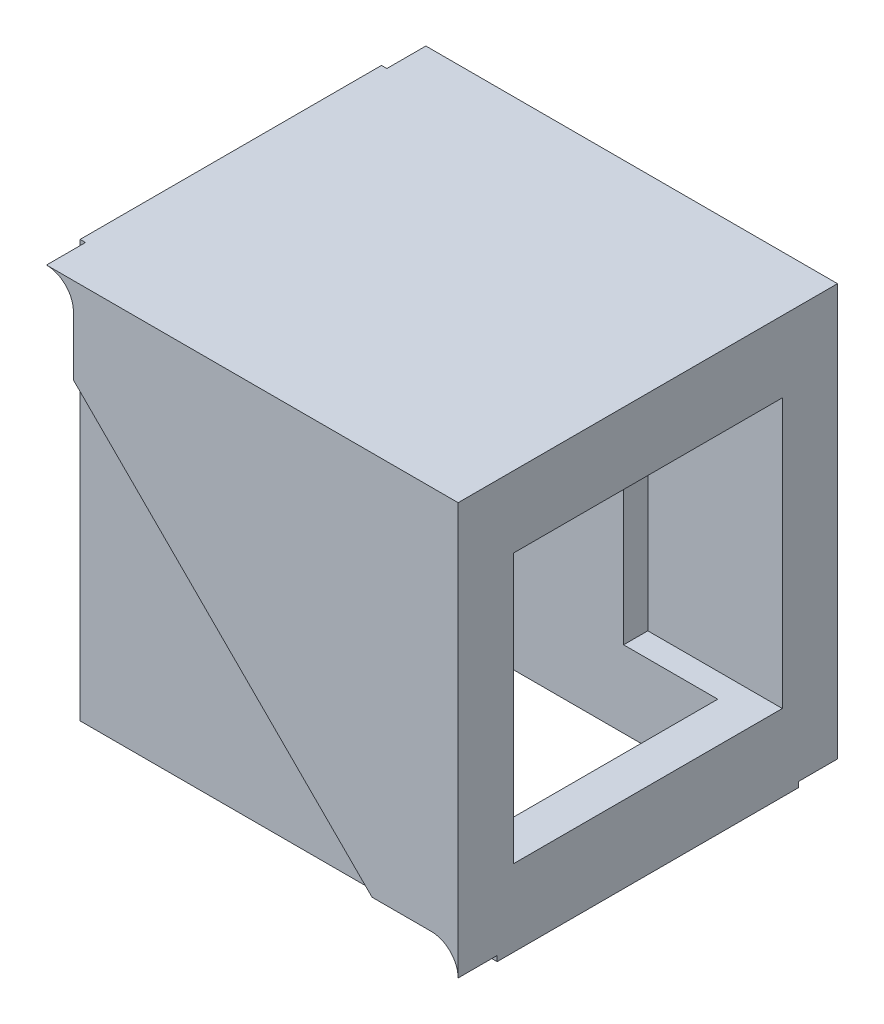
SolidWorks part; units mm, degrees
ref_plane "前视基准面" through (0, 0, 0) normal (0, 0, 1) x (1, 0, 0)
ref_plane "上视基准面" through (0, 0, 0) normal (0, 1, 0) x (1, 0, 0)
ref_plane "右视基准面" through (0, 0, 0) normal (1, 0, 0) x (0, 0, -1)
other "Configuration Table"
ref_plane "基准面1" through (835, 815, -2.8) normal (0, 0, 1) x (-1, 0, 0)
ref_plane "基准面2" through (835, 815, -25.2) normal (0, 0, 1) x (-1, 0, 0)
sketch "草图5" plane through (835, 815, -2.8) normal (0, 0, 1) x (-1, 0, 0)
  line L0 (831, 811) -> (831, 780) construction
  line L1 (800, 811) -> (831, 811) construction
  line L2 (831, 811) -> (831, 780)
  line L3 (800, 811) -> (831, 811)
  line L4 (831, 780) -> (800, 780)
  line L5 (800, 811) -> (800, 780)
extrude "凸台-拉伸1" add sketch "草图5" against normal blind 3
sketch "草图6" plane through (835, 815, -25.2) normal (0, 0, 1) x (-1, 0, 0)
  line L4 (831, 811) -> (800, 811)
  line L5 (831, 780) -> (831, 811)
  line L6 (800, 780) -> (831, 780)
  line L7 (800, 811) -> (800, 780)
  line L8 (831, 811) -> (800, 811)
  line L9 (831, 780) -> (831, 811)
  line L10 (800, 780) -> (831, 780)
  line L11 (800, 811) -> (800, 780)
  dimension "D1" = 0
extrude "凸台-拉伸2" add sketch "草图6" along normal blind 3 separate body
sketch "草图7" plane through (0, 0, -25.2) normal (0, 0, -1) x (-1, 0, 0)
  line L0 (-6.4, 28.6) -> (-28.6, 6.4) construction
  line L1 (-28.6, 6.4) -> (-33, 6.4) construction
  line L2 (-6.4, 28.6) -> (-28.6, 6.4)
  line L3 (-28.6, 6.4) -> (-33, 6.4)
  line L4 (-6.4, 28.6) -> (-6.4, 33) construction
  line L5 (-6.4, 28.6) -> (-6.4, 33)
  line L6 (-35, 4.4) -> (-35, 35)
  line L7 (-35, 35) -> (-4.4, 35)
  arc A0 (-33, 6.4) -> (-35, 4.4) centre (-33, 4.4) ccw construction
  arc A1 (-33, 6.4) -> (-35, 4.4) centre (-33, 4.4) ccw
  arc A2 (-4.4, 35) -> (-6.4, 33) centre (-4.4, 33) ccw construction
  arc A3 (-4.4, 35) -> (-6.4, 33) centre (-4.4, 33) ccw
extrude "凸台-拉伸3" add sketch "草图7" along normal blind 2.9
sketch "草图8" plane through (0, 0, -2.8) normal (0, 0, 1) x (1, 0, 0)
  line L5 (6.4, 33) -> (6.4, 28.6)
  line L6 (35, 35) -> (4.4, 35)
  line L7 (35, 4.4) -> (35, 35)
  line L8 (28.6, 6.4) -> (33, 6.4)
  line L9 (6.4, 28.6) -> (28.6, 6.4)
  line L10 (6.4, 33) -> (6.4, 28.6)
  line L11 (35, 35) -> (4.4, 35)
  line L12 (35, 4.4) -> (35, 35)
  line L13 (28.6, 6.4) -> (33, 6.4)
  line L14 (6.4, 28.6) -> (28.6, 6.4)
  arc A2 (6.4, 33) -> (4.4, 35) centre (4.4, 33) ccw
  arc A3 (35, 4.4) -> (33, 6.4) centre (33, 4.4) ccw
  arc A4 (6.4, 33) -> (4.4, 35) centre (4.4, 33) ccw
  arc A5 (35, 4.4) -> (33, 6.4) centre (33, 4.4) ccw
  dimension "D1" = 0
extrude "凸台-拉伸4" add sketch "草图8" along normal blind 2.9
sketch "草图9" plane through (0, 0, -5.8) normal (0, 0, -1) x (-1, 0, 0)
  line L11 (-35, 4) -> (-32, 4)
  line L12 (-35, 4) -> (-35, 35)
  line L14 (-35, 4) -> (-4, 4)
  line L15 (-4, 4) -> (-4, 35)
  line L16 (-4, 35) -> (-35, 35)
  line L17 (-35, 35) -> (-35, 4)
  line L18 (-35, 4) -> (-4, 4) construction
  line L19 (-4, 4) -> (-4, 35) construction
  line L20 (-4, 35) -> (-35, 35) construction
  line L21 (-35, 35) -> (-35, 4) construction
  line L22 (-32, 4) -> (-32, 32)
  line L23 (-4, 35) -> (-35, 35)
  line L24 (-4, 35) -> (-4, 32)
  line L25 (-4, 32) -> (-32, 32)
  point P2 (-35, 34.4042)
  dimension "D1" = 0
  dimension "D2" = 3
  dimension "D3" = 3
extrude "凸台-拉伸5" add sketch "草图9" along normal up to surface (16.4 mm away) up to face at (19.5, 19.5, -22.2)
sketch "草图10" plane through (35, 0, 0) normal (1, 0, 0) x (0, 0, -1)
  line L0 (4, 29.7) -> (4, 9.7)
  line L1 (24, 9.7) -> (4, 9.7)
  line L8 (28.1, 19.7) -> (-0.1, 19.7) construction
  line L9 (14, 4) -> (14, 35) construction
  line L10 (24, 29.7) -> (4, 29.7)
  line L11 (24, 29.7) -> (24, 9.7)
  line L16 (25.2, 4) -> (25.2, 4.4)
  line L17 (25.2, 4.4) -> (28.1, 4.4)
  line L18 (28.1, 4.4) -> (28.1, 35)
  line L19 (28.1, 35) -> (-0.1, 35)
  line L20 (-0.1, 35) -> (-0.1, 4.4)
  line L21 (-0.1, 4.4) -> (2.8, 4.4)
  line L22 (2.8, 4.4) -> (2.8, 4)
  line L23 (2.8, 4) -> (25.2, 4)
  line L24 (25.2, 4) -> (25.2, 4.4) construction
  line L25 (25.2, 4.4) -> (28.1, 4.4) construction
  line L26 (28.1, 4.4) -> (28.1, 35) construction
  line L27 (28.1, 35) -> (-0.1, 35) construction
  line L28 (-0.1, 35) -> (-0.1, 4.4) construction
  line L29 (-0.1, 4.4) -> (2.8, 4.4) construction
  line L30 (2.8, 4.4) -> (2.8, 4) construction
  line L31 (2.8, 4) -> (25.2, 4) construction
  dimension "D2" = 10
  dimension "D3" = 20
  dimension "D4" = 20
  dimension "D5" = 10
  dimension "D1" = 0
extrude "切除-拉伸1" cut sketch "草图10" against normal blind 10
